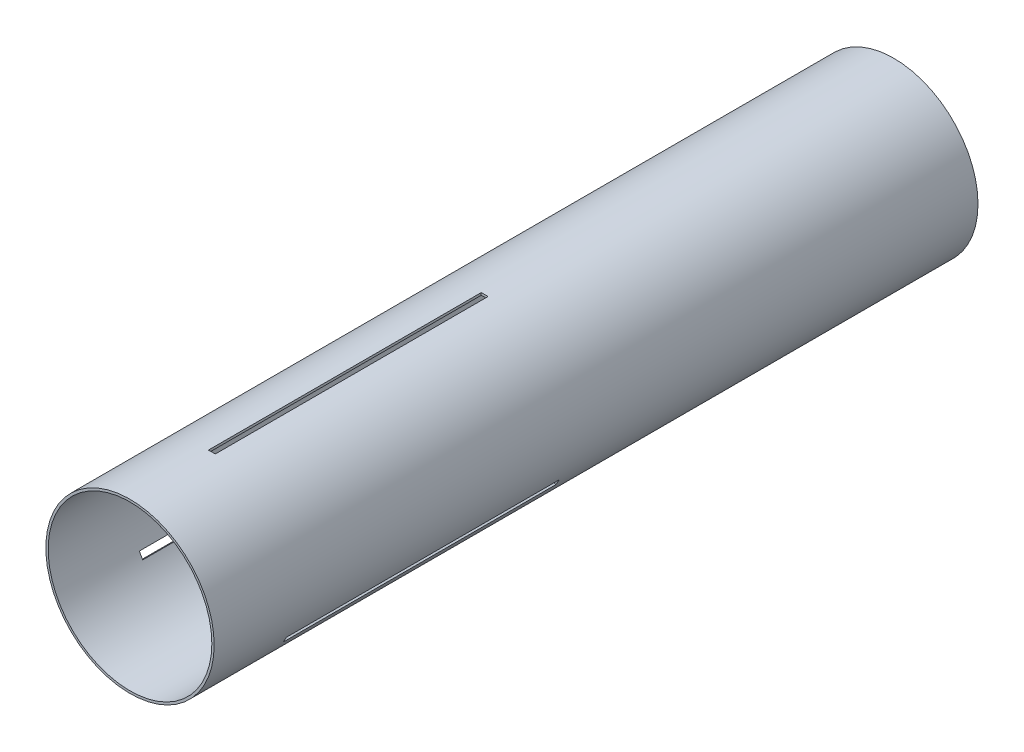
SolidWorks part; units mm, degrees
ref_plane "Plan de face" through (0, 0, 0) normal (0, 0, 1) x (1, 0, 0)
ref_plane "Plan de dessus" through (0, 0, 0) normal (0, 1, 0) x (1, 0, 0)
ref_plane "Plan de droite" through (0, 0, 0) normal (1, 0, 0) x (0, 0, -1)
sketch "Esquisse2" plane through (0, 0, 0) normal (0, 0, 1) x (1, 0, 0)
  circle A0 centre (0, 0) radius 78.359
  circle A1 centre (0, 0) radius 76.2
  dimension "D1" = 156.718
  dimension "D2" = 152.4
extrude "Boss.-Extru.1" add sketch "Esquisse2" along normal blind 711.2
sketch "Esquisse3" plane through (0, 0, 0) normal (0, 1, 0) x (1, 0, 0)
  line L0 (0, -711.2) -> (0, -635)
  line L1 (-78.359, -711.2) -> (78.359, -711.2) construction
  line L2 (0, -635) -> (0, -508)
  line L3 (0, -635) -> (-3.175, -635)
  line L5 (3.175, -381) -> (-3.175, -381)
  line L6 (3.175, -381) -> (3.175, -635)
  line L7 (3.175, -635) -> (-3.175, -635)
  line L8 (-3.175, -381) -> (-3.175, -635)
  line L9 (3.175, -381) -> (-3.175, -635) construction
  line L10 (3.175, -635) -> (-3.175, -381) construction
  dimension "D1" = 76.2
  dimension "D2" = 127
  dimension "D3" = 3.175
extrude "Enlèv. mat.-Extru.1" cut sketch "Esquisse3" along normal blind 153.416 contours L7 L6 L5 L8
pattern_circular "Répétition circulaire1" count 3 every 120 about axis through (0, 0, 0) along (0, 0, 1) of "Enlèv. mat.-Extru.1"
